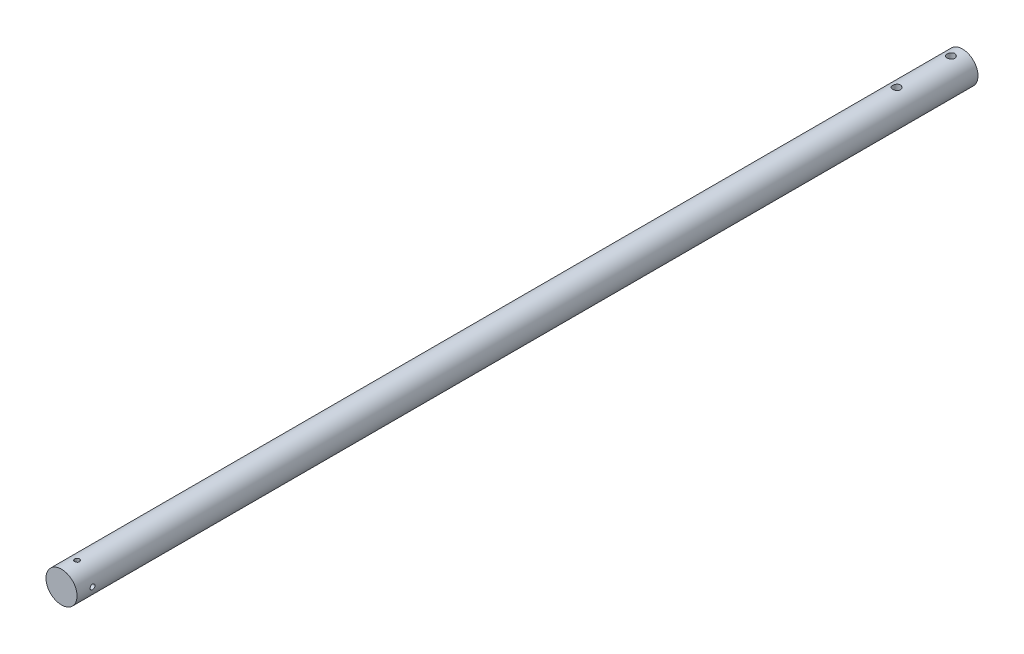
SolidWorks part; units mm, degrees
ref_plane "Front Plane" through (0, 0, 0) normal (0, 0, 1) x (1, 0, 0)
ref_plane "Top Plane" through (0, 0, 0) normal (0, 1, 0) x (1, 0, 0)
ref_plane "Right Plane" through (0, 0, 0) normal (1, 0, 0) x (0, 0, -1)
sketch "Sketch2" plane through (0, 0, 0) normal (0, 0, 1) x (1, 0, 0)
  line L1 (0, 0) -> (25.4, 0)
  line L2 (0, 0) -> (0, 25.4)
  line L3 (0, 25.4) -> (25.4, 25.4)
  line L4 (25.4, 0) -> (25.4, 25.4)
extrude "Boss-Extrude1" add sketch "Sketch2" along normal blind 736.6
sketch "Sketch4" plane through (0, 25.4, 0) normal (0, 1, 0) x (1, 0, 0)
  line L0 (12.7, 0) -> (12.7, -9.525)
  line L1 (25.4, 0) -> (0, 0) construction
  line L2 (12.7, -9.525) -> (12.7, -53.975)
  line L3 (12.7, -736.6) -> (12.7, -723.9)
  line L4 (25.4, -736.6) -> (0, -736.6) construction
  circle A0 centre (12.7, -9.525) radius 3.175
  circle A1 centre (12.7, -53.975) radius 3.175
  circle A2 centre (12.7, -723.9) radius 1.9844
extrude "Cut-Extrude1" cut sketch "Sketch4" against normal blind 736.6
sketch "Sketch5" plane through (25.4, 0, 0) normal (1, 0, 0) x (0, 0, -1)
  line L0 (-736.6, 12.7) -> (-723.9, 12.7)
  line L1 (-736.6, 0) -> (-736.6, 25.4) construction
  circle A0 centre (-723.9, 12.7) radius 1.9844
extrude "Cut-Extrude2" cut sketch "Sketch5" against normal blind 736.6 contours A0
sketch "Sketch6" plane through (0, 0, 736.6) normal (0, 0, 1) x (1, 0, 0)
  line L0 (0, 12.7) -> (25.4, 12.7)
  line L1 (0, 25.4) -> (0, 0) construction
  line L2 (25.4, 0) -> (25.4, 25.4) construction
  line L4 (0, 25.4) -> (25.4, 25.4)
  line L5 (0, 25.4) -> (0, 0)
  line L6 (0, 0) -> (25.4, 0)
  line L7 (25.4, 25.4) -> (25.4, 0)
  circle A0 centre (12.7, 12.7) radius 12.7
  line M1 (0, 25.4) -> (0, 0)
  line M2 (0, 0) -> (25.4, 0)
  line M3 (25.4, 0) -> (25.4, 25.4)
  line M4 (25.4, 25.4) -> (0, 25.4)
extrude "Cut-Extrude3" cut sketch "Sketch6" against normal blind 736.6 contours A0 L4 M1 | A0 M3 M4 | A0 L6 M3 | A0 M1 M2
